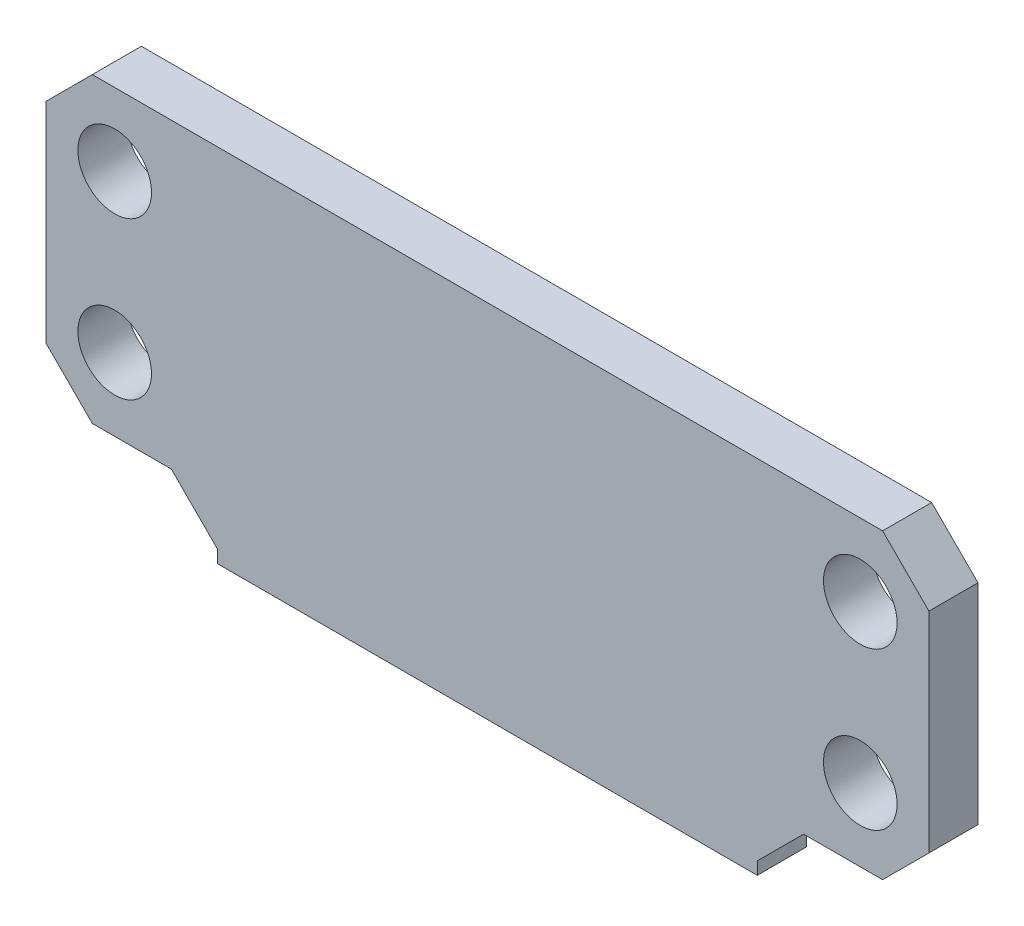
SolidWorks part; units mm, degrees
ref_plane "Front Plane" through (0, 0, 0) normal (0, 0, 1) x (1, 0, 0)
ref_plane "Top Plane" through (0, 0, 0) normal (0, 1, 0) x (1, 0, 0)
ref_plane "Right Plane" through (0, 0, 0) normal (1, 0, 0) x (0, 0, -1)
sketch "Sketch1" plane through (0, 0, 0) normal (0, 0, 1) x (1, 0, 0)
  line L0 (-17.4625, -10.541) -> (17.4625, -10.541) construction
  line L1 (17.4625, -21.209) -> (-17.4625, -21.209)
  line L2 (17.4625, -21.209) -> (17.4625, 1.651)
  line L3 (17.4625, 21.209) -> (-17.4625, 21.209)
  line L4 (-17.4625, -21.209) -> (-17.4625, 1.651)
  line L5 (17.4625, -21.209) -> (-17.4625, 21.209) construction
  line L6 (17.4625, 21.209) -> (-17.4625, -21.209) construction
  line L7 (0, 21.209) -> (0, -21.209) construction
  line L8 (-17.4625, 1.651) -> (17.4625, 1.651) construction
  line L9 (-17.4625, 6.35) -> (17.4625, 6.35) construction
  line L10 (-17.4625, 11.43) -> (17.4625, 11.43) construction
  line L11 (-17.4625, 11.43) -> (-17.4625, 1.651) construction
  line L12 (-17.4625, 5.4539) -> (-17.4625, 6.35)
  line L13 (28.575, 1.651) -> (17.4625, 1.651)
  line L14 (28.575, 1.651) -> (28.575, 21.209)
  line L15 (28.575, 21.209) -> (-28.575, 21.209)
  line L16 (-28.575, 1.651) -> (-28.575, 21.209)
  line L17 (28.575, 1.651) -> (-28.575, 21.209) construction
  line L18 (28.575, 21.209) -> (-28.575, 1.651) construction
  line L19 (17.4625, 5.4539) -> (17.4625, 6.35)
  line L20 (1.3594, 1.651) -> (-1.3594, 1.651)
  line L21 (-17.4625, 1.651) -> (-28.575, 1.651)
  circle A0 centre (-9.525, -10.541) radius 3.475
  circle A1 centre (9.525, -10.541) radius 3.475
  circle A2 centre (-24.13, 6.35) radius 2.3828
  circle A3 centre (-24.13, 16.51) radius 2.3828
  circle A4 centre (24.13, 16.51) radius 2.3828
  circle A5 centre (24.13, 6.35) radius 2.3828
  point P0 (0, 0)
  point P28 (0, 11.43)
  dimension "D4" = 9.525
  dimension "D7" = 9.779
  dimension "D1" = 34.925
  dimension "D2" = 42.418
  dimension "D3" = 10.668
  dimension "D5" = 22.86
  dimension "D6" = 4.699
  dimension "D8" = 24.13
  dimension "D9" = 57.15
extrude "Boss-Extrude1" add sketch "Sketch1" along normal blind 3.175
chamfer "Chamfer1" distance 3 angle 45 4 edges at (28.575, 21.209, 1.5875) (28.575, 1.651, 1.5875) (-28.575, 1.651, 1.5875) (-28.575, 21.209, 1.5875)
chamfer "Chamfer2" distance 3 angle 45 4 edges at (-17.4625, 1.651, 1.5875) (-17.4625, -21.209, 1.5875) (17.4625, 1.651, 1.5875) (17.4625, -21.209, 1.5875)
sketch "Sketch2" plane through (0, 0, 0) normal (0, 0, -1) x (-1, 0, 0)
  line L1 (-17.7176, -21.209) -> (18.3757, -21.209)
  line L2 (-17.7176, -21.209) -> (-17.7176, -2.159)
  line L3 (-17.7176, -2.159) -> (18.3757, -2.159)
  line L4 (18.3757, -21.209) -> (18.3757, -2.159)
  dimension "D1" = 19.05
extrude "Cut-Extrude1" cut sketch "Sketch2" against normal through all
